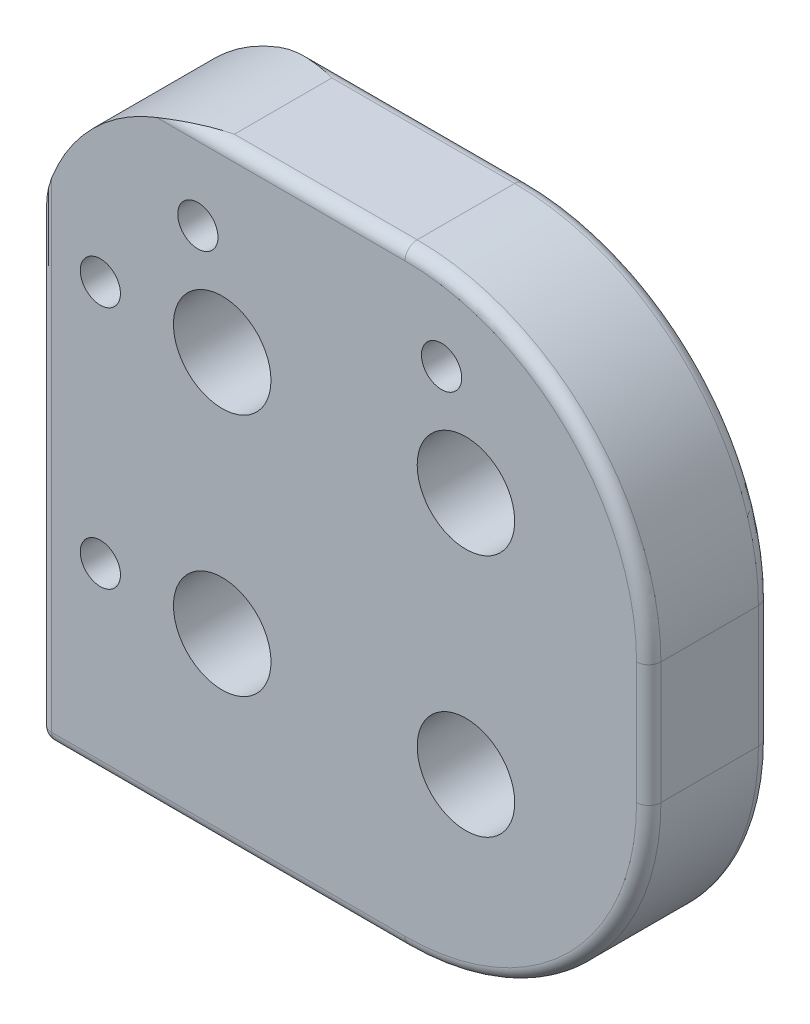
SolidWorks part; units mm, degrees
ref_plane "前视基准面" through (0, 0, 0) normal (0, 0, 1) x (1, 0, 0)
ref_plane "上视基准面" through (0, 0, 0) normal (0, 1, 0) x (1, 0, 0)
ref_plane "右视基准面" through (0, 0, 0) normal (1, 0, 0) x (0, 0, -1)
sketch "草图1" plane through (0, 0, 0) normal (0, 0, 1) x (1, 0, 0)
  line L1 (-25, -25) -> (25, -25) construction
  line L2 (-25, -25) -> (-25, 25)
  line L3 (-25, 25) -> (25, 25) construction
  line L4 (25, -25) -> (25, 25) construction
  line L5 (-25, -25) -> (25, 25) construction
  line L6 (-25, 25) -> (25, -25) construction
  line L7 (-25, 25) -> (25, 25)
  line L8 (-25, -25) -> (25, -25)
  line L9 (25, -25) -> (25, 25)
  point P0 (0, 0)
  dimension "D1" = 50
  dimension "D2" = 50
extrude "凸台-拉伸1" add sketch "草图1" along normal blind 10
sketch "草图2" plane through (0, 0, 10) normal (0, 0, 1) x (1, 0, 0)
  line L0 (0, 0) -> (50000, 0) construction
  line L7 (-10, -10) -> (-10, 10) construction
  line L8 (-10, 10) -> (15, 10) construction
  line L9 (15, -10) -> (15, 10) construction
  line L10 (-10, -10) -> (15, 10) construction
  line L11 (-10, 10) -> (15, -10) construction
  line L12 (2.5, 0) -> (2.5, 50000) construction
  line L13 (-10, -10) -> (15, -10) construction
  circle A4 centre (-10, 10) radius 1.6
  circle A5 centre (15, 10) radius 1.6
  circle A6 centre (15, -10) radius 1.6
  circle A7 centre (-10, -10) radius 1.6
  point P0 (2.5, 0)
  dimension "D3" = 2.5
  dimension "D4" = 3.2
  dimension "D1" = 20
  dimension "D2" = 25
extrude "切除-拉伸1" [suppressed] cut sketch "草图2" against normal through all
fillet "圆角1" radius 20 2 edges at (25, -25, 5) (25, 25, 5)
fillet "圆角2" radius 1 14 edges at (-10, -25, 0) (-10, -25, 10) (-25, 0, 0) (-10, 25, 0) (-10, 25, 10) (-25, 0, 10) (-25, -25, 5) (-25, 25, 5) (19.1421, -19.1421, 0) (25, 0, 0) (19.1421, 19.1421, 0) (19.1421, -19.1421, 10) (25, 0, 10) (19.1421, 19.1421, 10)
sketch "草图3" plane through (0, 0, 10) normal (0, 0, 1) x (1, 0, 0)
  line L0 (0, 30.5262) -> (0, -32.5462) construction
  line L1 (-34.1369, 0) -> (41.2066, 0) construction
  circle A0 centre (-10, 10) radius 4
  circle A1 centre (10, 10) radius 4
  circle A2 centre (10, -10) radius 4
  circle A3 centre (-10, -10) radius 4
  dimension "D1" = 8
  dimension "D2" = 10
  dimension "D3" = 10
extrude "切除-拉伸2" cut sketch "草图3" against normal blind 10
sketch "草图4" plane through (0, 0, 10) normal (0, 0, 1) x (1, 0, 0)
  line L1 (-10, 10) -> (10, 10) construction
  line L2 (-10, -10) -> (10, -10) construction
  circle A0 centre (-20, -10) radius 1.65
  circle A1 centre (-10, -10) radius 4 construction
  circle A2 centre (-20, 10) radius 1.65
  circle A4 centre (-10, 10) radius 4 construction
  circle A5 centre (-12, 18) radius 1.65
  circle A6 centre (8, 18) radius 1.65
  dimension "D1" = 3.3
  dimension "D2" = 10
  dimension "D3" = 3.3
  dimension "D4" = 10
  dimension "D5" = 3.3
  dimension "D6" = 3.3
  dimension "D7" = 20
  dimension "D8" = 2
  dimension "D9" = 8
extrude "切除-拉伸3" cut sketch "草图4" against normal blind 10
sketch "草图5" plane through (0, 0, 10) normal (0, 0, 1) x (1, 0, 0)
  line L1 (-25, 10) -> (-25, 6.2415)
  line L2 (-25, -24) -> (-25, 24) construction
  line L3 (-10, 25) -> (-27.0898, 25)
  line L4 (-27.0898, 25) -> (-25, 6.2415)
  arc A1 (-10, 25) -> (-25, 10) centre (-10, 10) ccw
  dimension "D1" = 15
extrude "切除-拉伸4" cut sketch "草图5" against normal blind 10
equation "\"3。2\"=3.16193"
